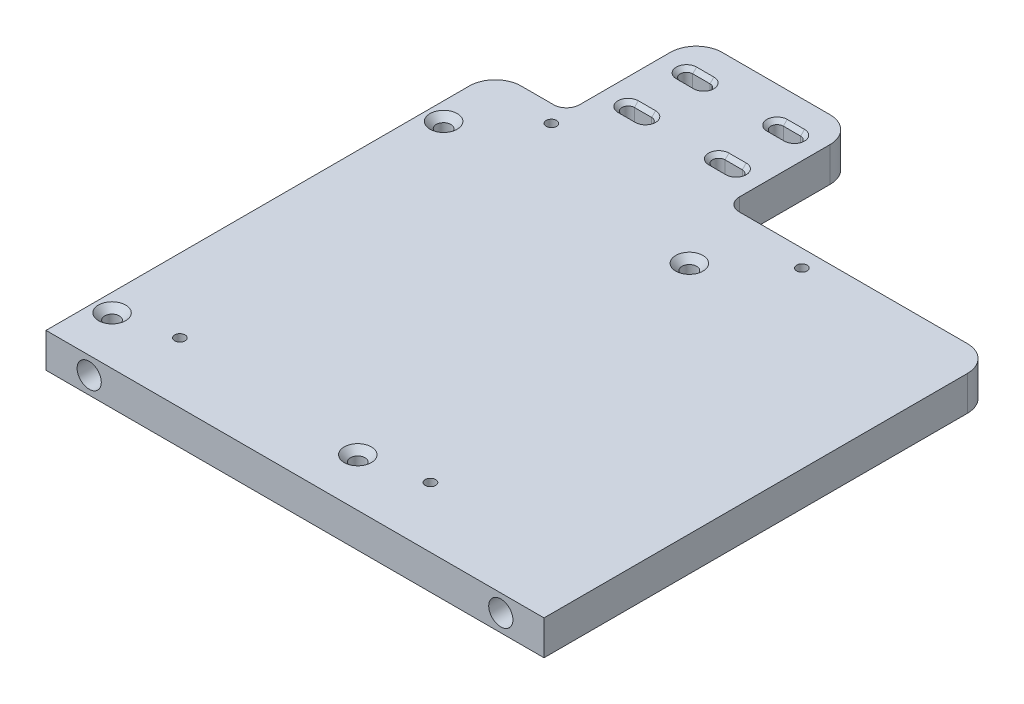
SolidWorks part; units mm, degrees
ref_plane "Front Plane" through (0, 0, 0) normal (0, 0, 1) x (1, 0, 0)
ref_plane "Top Plane" through (0, 0, 0) normal (0, 1, 0) x (1, 0, 0)
ref_plane "Right Plane" through (0, 0, 0) normal (1, 0, 0) x (0, 0, -1)
sketch "Sketch2" plane through (0, 0, 0) normal (0, 1, 0) x (1, 0, 0)
  line L0 (-4.4, 0) -> (4.4, 0) construction
  line L1 (-52.7926, 109.8893) -> (62.5, 109.8893)
  line L2 (-52.7926, 109.8893) -> (-52.7926, -24.1107)
  line L3 (-52.7926, -24.1107) -> (62.5, -24.1107)
  line L4 (62.5, 109.8893) -> (62.5, -24.1107)
  line L5 (0, -4.4) -> (0, 4.4) construction
  dimension "D1" = 109.8893
  dimension "D2" = 24.1107
  dimension "D3" = 62.5
  dimension "D4" = 52.7926
extrude "Boss-Extrude2" add sketch "Sketch2" along normal blind 8 contours L2 L1 L4 L3
sketch "Sketch3" plane through (0, 8, 0) normal (0, 1, 0) x (1, 0, 0)
  line L0 (-35.7926, 75.8893) -> (-35.7926, -10.1107) construction
  line L2 (-52.7926, -24.1107) -> (62.5, -24.1107) construction
  line L3 (-35.7926, -10.1107) -> (22.2074, -10.1107) construction
  line L6 (22.2074, 75.8893) -> (22.2074, -10.1107) construction
  line L7 (-35.7926, 75.8893) -> (22.2074, 75.8893) construction
  line L8 (0, -4.4) -> (0, 4.4) construction
  dimension "D1" = 22.2074
  dimension "D2" = 14
  dimension "D3" = 35.7926
  dimension "D4" = 100
fillet "Fillet2" radius 6 2 edges at (62.5, 4, -109.8893) (-52.7926, 4, -109.8893)
sketch "Sketch12" plane through (0, 0, 0) normal (0, -1, 0) x (-1, 0, 0)
  line L1 (52.7926, -24.1107) -> (-62.5, -24.1107) construction
  line L2 (0, 4.4) -> (0, -4.4) construction
  line L6 (-8.2274, -12.9507) -> (48.6626, -12.9507) construction
  line L9 (-8.2274, 63.8093) -> (48.6626, 63.8093) construction
  line L10 (48.6626, 63.8093) -> (48.6626, -12.9507) construction
  line L13 (-8.2274, 63.8093) -> (-8.2274, -12.9507) construction
  dimension "D1" = 11.16
  dimension "D2" = 76.76
  dimension "D3" = 8.2274
  dimension "D4" = 48.6626
hole_wizard "CSK for M2 Flat Head Machine Screw2" positions "Sketch15" profile "Sketch16" countersink size "M2" standard "ANSI Metric" end condition through all
sketch "Sketch15" plane through (0, 0, 0) normal (0, -1, 0) x (-1, 0, 0)
  line L0 (-22.2074, 75.8893) -> (-22.2074, -10.1107) construction
  point P0 (-22.2074, 75.8893)
  point P4 (35.7926, 75.8893)
  point P7 (35.7926, -10.1107)
  point P10 (-22.2074, -10.1107)
sketch "Sketch16" plane through (22.2074, 0, -75.8893) normal (1, 0, 0) x (0, 0, -1)
  line L0 (0, 0) -> (0, 8)
  line L1 (0, 8) -> (1.2, 8)
  line L2 (1.2, 8) -> (1.2, 1)
  line L3 (1.2, 1) -> (2.2, 0)
  line L5 (2.2, 0) -> (0, 0)
  line L6 (-1.2, 1) -> (-2.2, 0) construction
  line L11 (0, -6.35) -> (0, 107.95) construction
  dimension "Thru Hole Dia." = 2.4
  dimension "Thru Hole Depth" = 8
  dimension "Near C'Sink Dia." = 4.4
  dimension "Near C'Sink Angle" = 90
hole_wizard "CSK for M3 Flat Head Machine Screw1" positions "Sketch17" profile "Sketch18" countersink size "M3" standard "ANSI Metric" end condition through all
sketch "Sketch17" plane through (0, 8, 0) normal (0, 1, 0) x (1, 0, 0)
  point P0 (-48.6626, 63.8093)
  point P3 (8.2274, 63.8093)
  point P6 (8.2274, -12.9507)
  point P9 (-48.6626, -12.9507)
sketch "Sketch18" plane through (-48.6626, 8, -63.8093) normal (1, 0, 0) x (0, 0, 1)
  line L0 (0, 0) -> (0, 8)
  line L1 (0, 8) -> (1.7, 8)
  line L2 (1.7, 8) -> (1.7, 1.45)
  line L3 (1.7, 1.45) -> (3.15, 0)
  line L5 (3.15, 0) -> (0, 0)
  line L6 (-1.7, 1.45) -> (-3.15, 0) construction
  line L11 (0, -6.35) -> (0, 107.95) construction
  dimension "Thru Hole Dia." = 3.4
  dimension "Thru Hole Depth" = 8
  dimension "Near C'Sink Dia." = 6.3
  dimension "Near C'Sink Angle" = 90
sketch "Sketch19" plane through (-52.7926, 0, 0) normal (-1, 0, 0) x (0, 0, 1)
  line L0 (24.1107, 8) -> (24.1107, 0) construction
  line L1 (24.1107, -36) -> (32.1107, -36)
  line L2 (24.1107, -36) -> (24.1107, 63)
  line L3 (24.1107, 63) -> (32.1107, 63)
  line L4 (32.1107, -36) -> (32.1107, 63)
  line L5 (-103.8893, 8) -> (24.1107, 8) construction
  line L6 (-103.8893, 0) -> (24.1107, 0) construction
  dimension "D1" = 8
  dimension "D2" = 55
  dimension "D3" = 36
extrude "Boss-Extrude3" add sketch "Sketch19" against normal up to surface (115.2926 mm away) up to face at (62.5, 4, -39.8893)
sketch "Sketch21" plane through (0, 0, 32.1107) normal (0, 0, 1) x (1, 0, 0)
  line L0 (72.5, 73) -> (-62.7926, 73)
  line L1 (-62.7926, 73) -> (-62.7926, -56)
  line L2 (-62.7926, -56) -> (72.5, -56)
  line L3 (72.5, -56) -> (72.5, 73)
  line L4 (-52.7926, -36) -> (62.5, -36)
  line L5 (62.5, -36) -> (62.5, 63)
  line L6 (62.5, 63) -> (-52.7926, 63)
  line L7 (-52.7926, 63) -> (-52.7926, -36)
  line L8 (-52.7926, -36) -> (62.5, -36)
  line L9 (62.5, -36) -> (62.5, 63)
  line L10 (62.5, 63) -> (-52.7926, 63)
  line L11 (-52.7926, 63) -> (-52.7926, -36)
  line L12 (62.5, -36) -> (-52.7926, -36) construction
  dimension "D3" = 10
  dimension "D2" = 10
  dimension "D4" = 10
  dimension "D5" = 20
  dimension "D1" = 0
extrude "Boss-Extrude4" add sketch "Sketch21" against normal up to surface (8 mm away) up to face at (4.8537, 35.5, 24.1107)
fillet "Fillet3" radius 5 4 edges at (-62.7926, 73, 28.1107) (72.5, 73, 28.1107) (72.5, -56, 28.1107) (-62.7926, -56, 28.1107)
sketch "Sketch22" plane through (0, 0, 24.1107) normal (0, 0, -1) x (-1, 0, 0)
  line L0 (57.7926, 69.75) -> (-67.5, 69.75)
  line L1 (-69.25, 68) -> (-69.25, -51)
  line L2 (-67.5, -52.75) -> (57.7926, -52.75)
  line L3 (59.5426, -51) -> (59.5426, 68)
  line L4 (62.7926, -51) -> (62.7926, 68)
  line L5 (57.7926, 73) -> (-67.5, 73)
  line L6 (-72.5, 68) -> (-72.5, -51)
  line L7 (-67.5, -56) -> (57.7926, -56)
  line L8 (62.7926, -51) -> (62.7926, 68)
  line L9 (57.7926, 73) -> (-67.5, 73)
  line L10 (-72.5, 68) -> (-72.5, -51)
  line L11 (-67.5, -56) -> (57.7926, -56)
  arc A0 (-67.5, 69.75) -> (-69.25, 68) centre (-67.5, 68) ccw
  arc A1 (-69.25, -51) -> (-67.5, -52.75) centre (-67.5, -51) ccw
  arc A2 (57.7926, -52.75) -> (59.5426, -51) centre (57.7926, -51) ccw
  arc A3 (59.5426, 68) -> (57.7926, 69.75) centre (57.7926, 68) ccw
  arc A4 (62.7926, 68) -> (57.7926, 73) centre (57.7926, 68) ccw
  arc A5 (-67.5, 73) -> (-72.5, 68) centre (-67.5, 68) ccw
  arc A6 (-72.5, -51) -> (-67.5, -56) centre (-67.5, -51) ccw
  arc A7 (57.7926, -56) -> (62.7926, -51) centre (57.7926, -51) ccw
  arc A8 (62.7926, 68) -> (57.7926, 73) centre (57.7926, 68) ccw
  arc A9 (-67.5, 73) -> (-72.5, 68) centre (-67.5, 68) ccw
  arc A10 (-72.5, -51) -> (-67.5, -56) centre (-67.5, -51) ccw
  arc A11 (57.7926, -56) -> (62.7926, -51) centre (57.7926, -51) ccw
  dimension "D1" = 0
  dimension "D2" = 3.25
extrude "Cut-Extrude1" cut sketch "Sketch22" against normal blind 4
sketch "Sketch24" plane through (0, 0, 24.1107) normal (0, 0, -1) x (-1, 0, 0)
  line L0 (-62.5, 8) -> (-62.5, 69.75) construction
  line L1 (57.7926, 69.75) -> (-67.5, 69.75) construction
  line L2 (52.7926, 8) -> (52.7926, 69.75) construction
  line L3 (-62.5, 55) -> (52.7926, 55) construction
  line L4 (52.7926, 8) -> (-62.5, 8) construction
  line L6 (-62.5, 55) -> (52.7926, 55)
  line L7 (-62.5, 55) -> (-62.5, 65)
  line L8 (-62.5, 65) -> (52.7926, 65)
  line L9 (52.7926, 55) -> (52.7926, 65)
  dimension "D1" = 47
  dimension "D2" = 10
extrude "Boss-Extrude5" add sketch "Sketch24" along normal blind 104
fillet "Fillet4" radius 6 2 edges at (62.5, 60, -79.8893) (-52.7926, 60, -79.8893)
hole_wizard "M2.5 Clearance Hole1" positions "Sketch58" profile "Sketch59" hole size "M2.5" standard "ANSI Metric" end condition through all
sketch "Sketch58" plane through (0, 8, 0) normal (0, 1, 0) x (1, 0, 0)
  line L0 (-28.27, 101.64) -> (-7.29, 101.64) construction
  line L1 (-7.29, 101.64) -> (-7.29, 88.14) construction
  line L2 (-7.29, 88.14) -> (-28.27, 88.14) construction
  line L3 (-28.27, 88.14) -> (-28.27, 101.64) construction
  line L6 (-4.4, 0) -> (4.4, 0) construction
  line L7 (0, -4.4) -> (0, 4.4) construction
  point P0 (-28.27, 101.64)
  point P2 (-7.29, 101.64)
  point P4 (-7.29, 88.14)
  point P6 (-28.27, 88.14)
  dimension "D1" = 88.14
  dimension "D2" = 28.27
  dimension "D3" = 7.29
  dimension "D4" = 101.64
sketch "Sketch59" plane through (-28.27, 8, -101.64) normal (1, 0, 0) x (0, 0, 1)
  line L0 (0, 0) -> (0, 64)
  line L1 (0, 64) -> (1.45, 64)
  line L2 (1.45, 64) -> (1.45, 0)
  line L5 (1.45, 0) -> (0, 0)
  line L11 (0, -6.35) -> (0, 107.95) construction
  dimension "Thru Hole Dia." = 2.9
  dimension "Thru Hole Depth" = 64
sketch "Sketch60" plane through (0, 8, 0) normal (0, 1, 0) x (1, 0, 0)
  line L0 (-30.27, 101.64) -> (-26.27, 101.64) construction
  line L1 (-30.27, 103.09) -> (-26.27, 103.09)
  line L2 (-30.27, 100.19) -> (-26.27, 100.19)
  line L3 (-9.29, 101.64) -> (-5.29, 101.64) construction
  line L4 (-9.29, 103.09) -> (-5.29, 103.09)
  line L5 (-9.29, 100.19) -> (-5.29, 100.19)
  line L6 (-30.27, 88.14) -> (-26.27, 88.14) construction
  line L7 (-30.27, 89.59) -> (-26.27, 89.59)
  line L8 (-30.27, 86.69) -> (-26.27, 86.69)
  line L9 (-9.29, 88.14) -> (-5.29, 88.14) construction
  line L10 (-9.29, 89.59) -> (-5.29, 89.59)
  line L11 (-9.29, 86.69) -> (-5.29, 86.69)
  arc A0 (-30.27, 103.09) -> (-30.27, 100.19) centre (-30.27, 101.64) ccw
  arc A1 (-26.27, 100.19) -> (-26.27, 103.09) centre (-26.27, 101.64) ccw
  arc A2 (-9.29, 103.09) -> (-9.29, 100.19) centre (-9.29, 101.64) ccw
  arc A3 (-5.29, 100.19) -> (-5.29, 103.09) centre (-5.29, 101.64) ccw
  arc A4 (-30.27, 89.59) -> (-30.27, 86.69) centre (-30.27, 88.14) ccw
  arc A5 (-26.27, 86.69) -> (-26.27, 89.59) centre (-26.27, 88.14) ccw
  arc A6 (-9.29, 89.59) -> (-9.29, 86.69) centre (-9.29, 88.14) ccw
  arc A7 (-5.29, 86.69) -> (-5.29, 89.59) centre (-5.29, 88.14) ccw
  circle A8 centre (-28.27, 101.64) radius 1.45 construction
  point P2 (-28.27, 101.64)
  point P9 (-7.29, 101.64)
  point P17 (-28.27, 88.14)
  point P25 (-7.29, 88.14)
  dimension "D1" = 4
extrude "Cut-Extrude4" cut sketch "Sketch60" against normal up to next
chamfer "Chamfer1" distance 0.9 angle 45 16 edges at (-7.29, 8, -100.19) (-3.84, 8, -101.64) (-10.74, 8, -101.64) (-7.29, 8, -103.09) (-7.29, 8, -86.69) (-3.84, 8, -88.14) (-10.74, 8, -88.14) (-7.29, 8, -89.59) (-28.27, 8, -86.69) (-24.82, 8, -88.14) (-31.72, 8, -88.14) (-28.27, 8, -89.59) (-28.27, 8, -103.09) (-31.72, 8, -101.64) (-24.82, 8, -101.64) (-28.27, 8, -100.19)
sketch "Sketch61" plane through (-52.7926, 0, 0) normal (-1, 0, 0) x (0, 0, 1)
  line L0 (-73.8893, 55) -> (24.1107, 55) construction
  line L1 (24.1107, 65) -> (-79.8893, 65)
  line L2 (24.1107, 65) -> (24.1107, 55)
  line L3 (24.1107, 55) -> (-79.8893, 55)
  line L4 (-79.8893, 65) -> (-79.8893, 55)
  line L5 (-79.8893, 55) -> (-79.8893, 65) construction
extrude "Cut-Extrude6" cut sketch "Sketch61" against normal up to surface (115.2926 mm away) up to face at (62.5, 60, -24.8893)
sketch "Sketch62" plane through (-62.7926, 0, 0) normal (-1, 0, 0) x (0, 0, 1)
  line L0 (32.1107, 68) -> (32.1107, -51) construction
  line L1 (32.1107, -56) -> (24.1107, -56)
  line L2 (32.1107, -56) -> (32.1107, 73)
  line L3 (32.1107, 73) -> (24.1107, 73)
  line L4 (24.1107, -56) -> (24.1107, 73)
  line L5 (24.1107, -51) -> (24.1107, 68) construction
  line L6 (28.1107, 73) -> (32.1107, 73) construction
  line L7 (32.1107, -56) -> (28.1107, -56) construction
extrude "Cut-Extrude7" cut sketch "Sketch62" against normal up to surface (135.2926 mm away) up to face at (72.5, 8.5, 30.1107)
hole_wizard "Ø5.6 (5.6) Diameter Hole1" positions "Sketch63" profile "Sketch65" hole size "Ø5.6" standard "ANSI Metric"
sketch "Sketch63" plane through (0, 0, 24.1107) normal (0, 0, 1) x (1, 0, 0)
  line L0 (-52.7926, 8) -> (-52.7926, 0) construction
  line L1 (-52.7926, 8) -> (62.5, 8) construction
  line L2 (62.5, 0) -> (62.5, 8) construction
  point P0 (-42.7926, 4)
  point P2 (52.5, 4)
  dimension "D1" = 10
  dimension "D2" = 4
  dimension "D3" = 10
sketch "Sketch65" plane through (-42.7926, 4, 24.1107) normal (1, 0, 0) x (0, -1, 0)
  line L0 (0, 0) -> (0, 9.6824)
  line L1 (0, 9.6824) -> (2.8, 8)
  line L2 (2.8, 8) -> (2.8, 0)
  line L5 (2.8, 0) -> (0, 0)
  line L10 (0, 9.6824) -> (-2.8, 8) construction
  line L11 (0, -6.35) -> (0, 107.95) construction
  dimension "Hole Dia." = 5.6
  dimension "Hole Depth" = 8
  dimension "Drill Angle" = 118
sketch "Sketch66" plane through (0, 0, 0) normal (0, -1, 0) x (1, 0, 0)
  line L0 (62.5, -103.8893) -> (62.5, 24.1107) construction
  line L1 (0.71, -79.8893) -> (62.5, -79.8893)
  line L2 (0.71, -79.8893) -> (0.71, -109.8893)
  line L3 (0.71, -109.8893) -> (62.5, -109.8893)
  line L4 (62.5, -79.8893) -> (62.5, -109.8893)
  line L5 (-46.7926, -109.8893) -> (56.5, -109.8893) construction
  line L6 (-52.7926, 24.1107) -> (62.5, 24.1107) construction
  dimension "D1" = 6
  dimension "D2" = 104
sketch "Sketch67" plane through (0, 0, 0) normal (0, -1, 0) x (-1, 0, 0)
  line L0 (46.7926, 109.8893) -> (-56.5, 109.8893) construction
  line L1 (36.27, 79.8893) -> (52.7926, 79.8893)
  line L2 (36.27, 79.8893) -> (36.27, 109.8893)
  line L3 (36.27, 109.8893) -> (52.7926, 109.8893)
  line L4 (52.7926, 79.8893) -> (52.7926, 109.8893)
  line L5 (52.7926, 103.8893) -> (52.7926, -24.1107) construction
  line L8 (52.7926, -24.1107) -> (-62.5, -24.1107) construction
  dimension "D1" = 104
  dimension "D2" = 6
extrude "Cut-Extrude9" cut sketch "Sketch66" against normal up to surface (8 mm away) up to face at (-7.29, 8, -101.64)
extrude "Cut-Extrude10" cut sketch "Sketch67" against normal up to surface (8 mm away) up to face at (-7.29, 8, -101.64)
fillet "Fillet5" radius 6 4 edges at (-52.7926, 4, -79.8893) (-36.27, 4, -109.8893) (0.71, 4, -109.8893) (62.5, 4, -79.8893)
fillet "Fillet6" radius 3 2 edges at (0.71, 4, -79.8893) (-36.27, 4, -79.8893)
